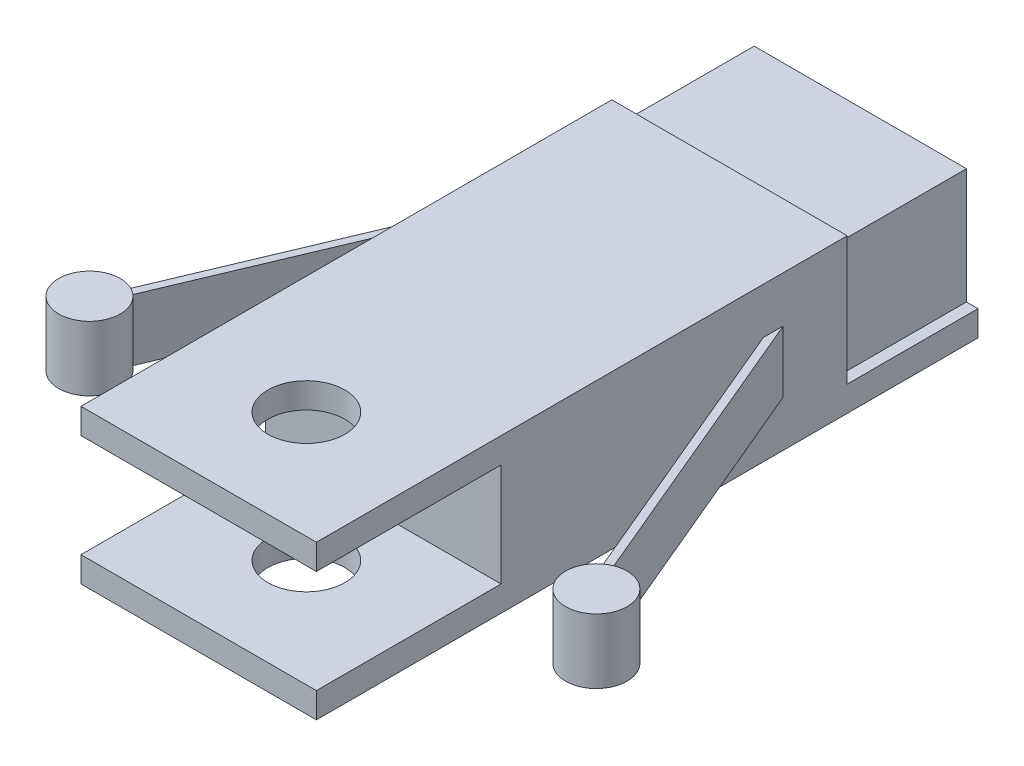
SolidWorks part; units mm, degrees
ref_plane "Front Plane" through (0, 0, 0) normal (0, 0, 1) x (1, 0, 0)
ref_plane "Top Plane" through (0, 0, 0) normal (0, 1, 0) x (1, 0, 0)
ref_plane "Right Plane" through (0, 0, 0) normal (1, 0, 0) x (0, 0, -1)
sketch "Sketch1" plane through (0, 0, 0) normal (0, 1, 0) x (1, 0, 0)
  line L1 (-7.65, 21.5) -> (7.65, 21.5)
  line L2 (-7.65, 21.5) -> (-7.65, -21.5)
  line L3 (-7.65, -21.5) -> (7.65, -21.5)
  line L4 (7.65, 21.5) -> (7.65, -21.5)
  line L5 (-7.65, 21.5) -> (7.65, -21.5) construction
  line L6 (-7.65, -21.5) -> (7.65, 21.5) construction
  point P0 (0, 0)
  dimension "D1" = 15.3
  dimension "D2" = 43
extrude "Boss-Extrude1" add sketch "Sketch1" along normal blind 10 contours L2 L3 L4 L1
sketch "Sketch2" plane through (7.65, 0, 0) normal (1, 0, 0) x (0, 0, -1)
  line L0 (-21.5, 10) -> (-21.5, 0) construction
  line L1 (-21.5, 8.35) -> (-9.5, 8.35)
  line L2 (-21.5, 8.35) -> (-21.5, 1.65)
  line L3 (-21.5, 1.65) -> (-9.5, 1.65)
  line L4 (-9.5, 8.35) -> (-9.5, 1.65)
  line L5 (21.5, 10) -> (-21.5, 10) construction
  line L6 (55, 0) -> (-55, 0) construction
  line L7 (21.5, 10) -> (21.5, 0) construction
  line L8 (13, 10) -> (21.5, 10)
  line L9 (13, 10) -> (13, 1.65)
  line L10 (13, 1.65) -> (21.5, 1.65)
  line L11 (21.5, 10) -> (21.5, 1.65)
  dimension "D1" = 1.65
  dimension "D2" = 1.65
  dimension "D3" = 1.65
  dimension "D4" = 34.5
  dimension "D5" = 12
extrude "Cut-Extrude1" cut sketch "Sketch2" against normal through all
sketch "Sketch3" plane through (0, 1.65, 0) normal (0, 1, 0) x (1, 0, 0)
  line L1 (-6.9, 21.5) -> (6.9, 21.5)
  line L2 (-6.9, 21.5) -> (-6.9, 13.5)
  line L3 (-6.9, 13.5) -> (6.9, 13.5)
  line L4 (6.9, 21.5) -> (6.9, 13.5)
  line L5 (-7.65, 21.5) -> (7.65, 21.5) construction
  line L6 (-7.65, 13) -> (-7.65, 21.5) construction
  line L7 (7.65, 13) -> (7.65, 21.5) construction
  dimension "D1" = 8
  dimension "D2" = 0.75
  dimension "D3" = 0.75
extrude "Boss-Extrude2" add sketch "Sketch3" along normal blind 7.5 separate body contours L4 L3 L2 L1
sketch "Sketch4" plane through (0, 0, -21.5) normal (0, 0, -1) x (-1, 0, 0)
  line L0 (-6.4, 1.65) -> (-6.4, 7.65)
  line L1 (6.9, 1.65) -> (-6.9, 1.65) construction
  line L2 (-6.4, 7.65) -> (-5.6, 7.65)
  line L3 (-5.6, 7.65) -> (-6.4, 8.65)
  line L4 (-6.4, 8.65) -> (-2.4667, 8.65)
  line L5 (-2.4667, 8.65) -> (-3.2667, 7.65)
  line L6 (-3.2667, 7.65) -> (-2.4667, 7.65)
  line L7 (-2.4667, 7.65) -> (-2.4667, 1.65)
  line L8 (7.65, 1.65) -> (-7.65, 1.65) construction
  line L9 (-2.4667, 1.65) -> (-6.4, 1.65)
  line L10 (-6.9, 9.15) -> (-6.9, 1.65) construction
  dimension "D1" = 0.5
  dimension "D2" = 3.9333
  dimension "D3" = 3.9333
  dimension "D4" = 0.8
  dimension "D5" = 0.8
  dimension "D6" = 7
  dimension "D7" = 6
extrude "Cut-Extrude2" cut sketch "Sketch4" against normal blind 7.5 contours L3 L4 L5 L6 L7 L9 L0 L2
pattern_linear "LPattern1" count 3 spacing 4.4333 along (-1, 0, 0) of "Cut-Extrude2"
ref_plane "Plane1" through (0, 3, 0) normal (0, 1, 0) x (1, 0, 0)
sketch "Sketch6" plane through (0, 3, 0) normal (0, 1, 0) x (1, 0, 0)
  line L0 (-6.7763, 10.9174) -> (-16.4718, -12.1259)
  line L1 (-16.4718, -12.1259) -> (-16.011, -12.3198)
  line L2 (-16.011, -12.3198) -> (-6.3155, 10.7235)
  line L3 (-6.3155, 10.7235) -> (-6.7763, 10.9174)
  dimension "D1" = 25
  dimension "D2" = 0.5
extrude "Boss-Extrude3" add sketch "Sketch6" along normal blind 4 separate body contours L0 L1 L2 L3
sketch "Sketch7" plane through (0, 3, 0) normal (0, 1, 0) x (1, 0, 0)
  circle A0 centre (-16.4718, -12.1259) radius 2
  dimension "D1" = 4
extrude "Boss-Extrude4" add sketch "Sketch7" along normal blind 4.1 and the other way blind 0.1 separate body
sketch "Sketch8" plane through (0, 0, 0) normal (0, -1, 0) x (1, 0, 0)
  line L0 (0, -5.5) -> (0, 5.5) construction
  line L1 (-7.65, 21.5) -> (7.65, 21.5) construction
  circle A0 centre (0, 14.5) radius 2.5
  dimension "D1" = 5
  dimension "D2" = 7
extrude "Cut-Extrude3" cut sketch "Sketch8" against normal through all contours A0
mirror "Mirror1" about plane through (0, 0, 0) normal (1, 0, 0) of bodies 107 106
